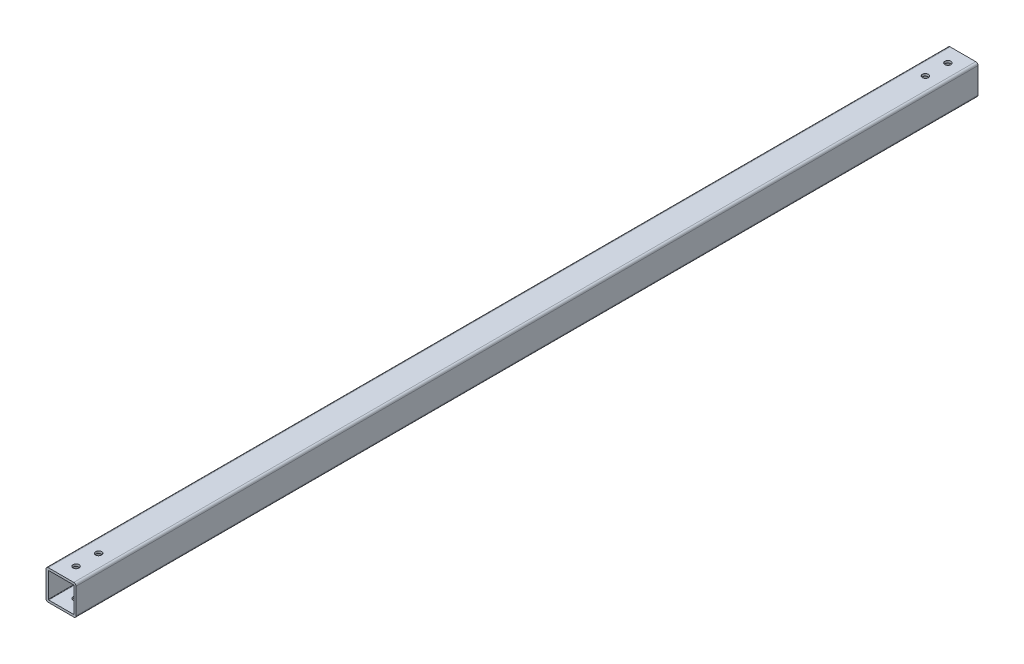
SolidWorks part; units mm, degrees
ref_plane "Front Plane" through (0, 0, 0) normal (0, 0, 1) x (1, 0, 0)
ref_plane "Top Plane" through (0, 0, 0) normal (0, 1, 0) x (1, 0, 0)
ref_plane "Right Plane" through (0, 0, 0) normal (1, 0, 0) x (0, 0, -1)
sketch "Sketch1" plane through (0, 0, 0) normal (0, 0, 1) x (1, 0, 0)
  line L1 (-20, 20) -> (20, 20)
  line L2 (-20, 20) -> (-20, -20)
  line L3 (-20, -20) -> (20, -20)
  line L4 (20, 20) -> (20, -20)
  line L5 (-20, 20) -> (20, -20) construction
  line L6 (-20, -20) -> (20, 20) construction
  point P0 (0, 0)
  dimension "D1" = 40
  dimension "D2" = 40
extrude "Extrude-Thin1" add sketch "Sketch1" along normal blind 1200 thin
fillet "Fillet1" radius 0.5 4 edges at (-17, -17, 600) (-17, 17, 600) (17, 17, 600) (17, -17, 600)
fillet "Fillet2" radius 3 4 edges at (20, -20, 600) (-20, -20, 600) (20, 20, 600) (-20, 20, 600)
hole_wizard "Ø8.0 (8) Diameter Hole1" positions "Sketch4" profile "Sketch3" hole size "Ø8.0" standard "ANSI Metric" end condition through all
sketch "Sketch4" plane through (0, 20, 0) normal (0, 1, 0) x (1, 0, 0)
  line L0 (0, -1200) -> (0, 0) construction
  line L1 (17, -1200) -> (-17, -1200) construction
  point P10 (0, -1180)
  point P12 (0, -20)
  dimension "D1" = 20
  dimension "D2" = 20
sketch "Sketch3" plane through (0, 20, 1180) normal (1, 0, 0) x (0, 0, 1)
  line L0 (0, 0) -> (0, 40)
  line L1 (0, 40) -> (4, 40)
  line L2 (4, 40) -> (4, 0)
  line L5 (4, 0) -> (0, 0)
  line L11 (0, -6.35) -> (0, 107.95) construction
  dimension "Thru Hole Dia." = 8
  dimension "Thru Hole Depth" = 40
sketch "Sketch5" plane through (0, 20, 0) normal (0, 1, 0) x (1, 0, 0)
  line L0 (172.9723, -600) -> (-208.9573, -600) construction
  line L1 (17, 0) -> (-17, 0) construction
  line L2 (20, 0) -> (20, -1200) construction
  circle A0 centre (0, -1150) radius 4
  circle A1 centre (0, -1180) radius 4 construction
  circle A2 centre (0, -50) radius 4
  dimension "D1" = 30
  dimension "D2" = 8
  dimension "D3" = 600
  dimension "D4" = 20
extrude "Cut-Extrude1" cut sketch "Sketch5" against normal through all
equation "\"a\"= \"Beam Profile@Plasma Beta.Assembly\""
equation "\"b\"= 3"
equation "\"L\"= \"Width@Plasma Beta.Assembly\""
equation "\"D2@Sketch1\"=\"a\""
equation "\"D1@Sketch1\"=\"a\""
equation "\"D1@Extrude-Thin1\"=\"L\""
equation "\"D5@Extrude-Thin1\"=\"b\""
equation "\"D1@Fillet2\"=\"b\""
